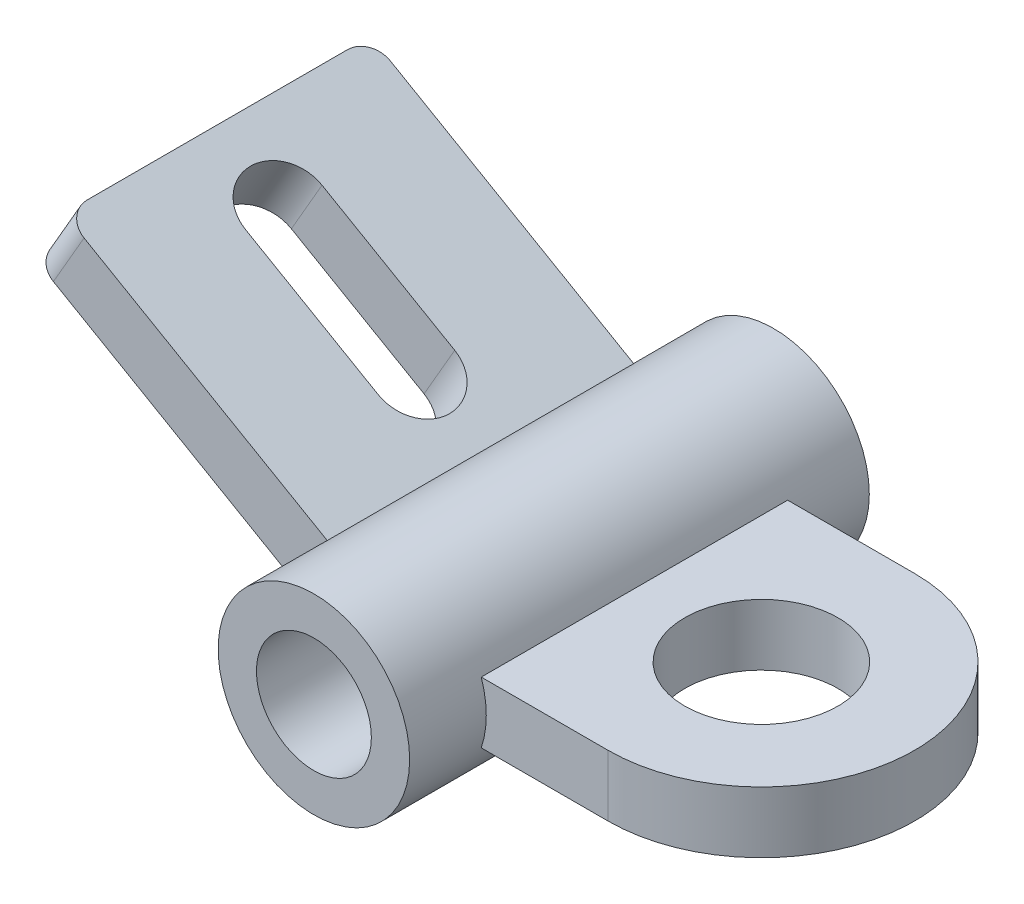
SolidWorks part; units mm, degrees
ref_plane "Front Plane" through (0, 0, 0) normal (0, 0, 1) x (1, 0, 0)
ref_plane "Top Plane" through (0, 0, 0) normal (0, 1, 0) x (1, 0, 0)
ref_plane "Right Plane" through (0, 0, 0) normal (1, 0, 0) x (0, 0, -1)
sketch "Sketch2" plane through (0, 0, 0) normal (0, 1, 0) x (1, 0, 0)
  line L0 (0, 27.8023) -> (0, -12.1977)
  line L1 (0, 27.8023) -> (19.5, 27.8023)
  line L2 (0, -12.1977) -> (19.5, -12.1977)
  arc A0 (19.5, 27.8023) -> (19.5, -12.1977) centre (19.5, 7.8023) cw
  circle A1 centre (19.5, 7.8023) radius 10
  dimension "D2" = 20
  dimension "D3" = 20
  dimension "D1" = 19.5
extrude "Boss-Extrude1" add sketch "Sketch2" against normal blind 8
sketch "Sketch3" plane through (0, 0, 12.1977) normal (0, 0, 1) x (1, 0, 0)
  circle A0 centre (-8.9109, -4) radius 12.5
  circle A1 centre (-8.9109, -4) radius 7.5
  dimension "D1" = 25
  dimension "D2" = 15
extrude "Boss-Extrude2" add sketch "Sketch3" against normal blind 50
sketch "Sketch4" plane through (0, 0, 12.1977) normal (0, 0, 1) x (1, 0, 0)
  circle A0 centre (-8.9109, -4) radius 7.5
  circle A1 centre (-8.9109, -4) radius 12.5
extrude "Boss-Extrude3" add sketch "Sketch4" along normal blind 10
ref_plane "Plane1" through (0, 0, 12.1977) normal (0, 0, 1) x (1, 0, 0)
sketch "Sketch6" plane through (0, 0, 12.1977) normal (0, 0, 1) x (1, 0, 0)
  line L0 (-8.9109, -4) -> (-54.6365, 22.3997) construction
  line L1 (-8.9109, -4) -> (-55.5331, -4) construction
  line L2 (-18.0325, -3.3524) -> (-55.5112, 18.2859)
  line L3 (-55.5112, 18.2859) -> (-51.5112, 25.2141)
  line L4 (-51.5112, 25.2141) -> (-14.0325, 3.5758)
  line L5 (-14.0325, 3.5758) -> (-18.0325, -3.3524)
  dimension "D1" = 30
  dimension "D2" = 51.5
  dimension "D3" = 4
  dimension "D4" = 4
extrude "Boss-Extrude4" add sketch "Sketch6" against normal blind 40
sketch "Sketch7" plane through (-1.9598, -3.3944, 0) normal (0.5, 0.866, 0) x (0.866, -0.5, 0)
  line L0 (-47.217, 7.8023) -> (-27.217, 7.8023) construction
  line L1 (-47.217, 12.8023) -> (-27.217, 12.8023)
  line L2 (-47.217, 2.8023) -> (-27.217, 2.8023)
  line L3 (-57.217, 27.8023) -> (-57.217, -12.1977) construction
  arc A0 (-47.217, 12.8023) -> (-47.217, 2.8023) centre (-47.217, 7.8023) ccw
  arc A1 (-27.217, 2.8023) -> (-27.217, 12.8023) centre (-27.217, 7.8023) ccw
  point P2 (-37.217, 7.8023)
  dimension "D2" = 5
  dimension "D1" = 20
  dimension "D3" = 10
extrude "Cut-Extrude1" cut sketch "Sketch7" against normal through all
fillet "Fillet1" radius 3 2 edges at (-53.5112, 21.75, -27.8023) (-53.5112, 21.75, 12.1977)
